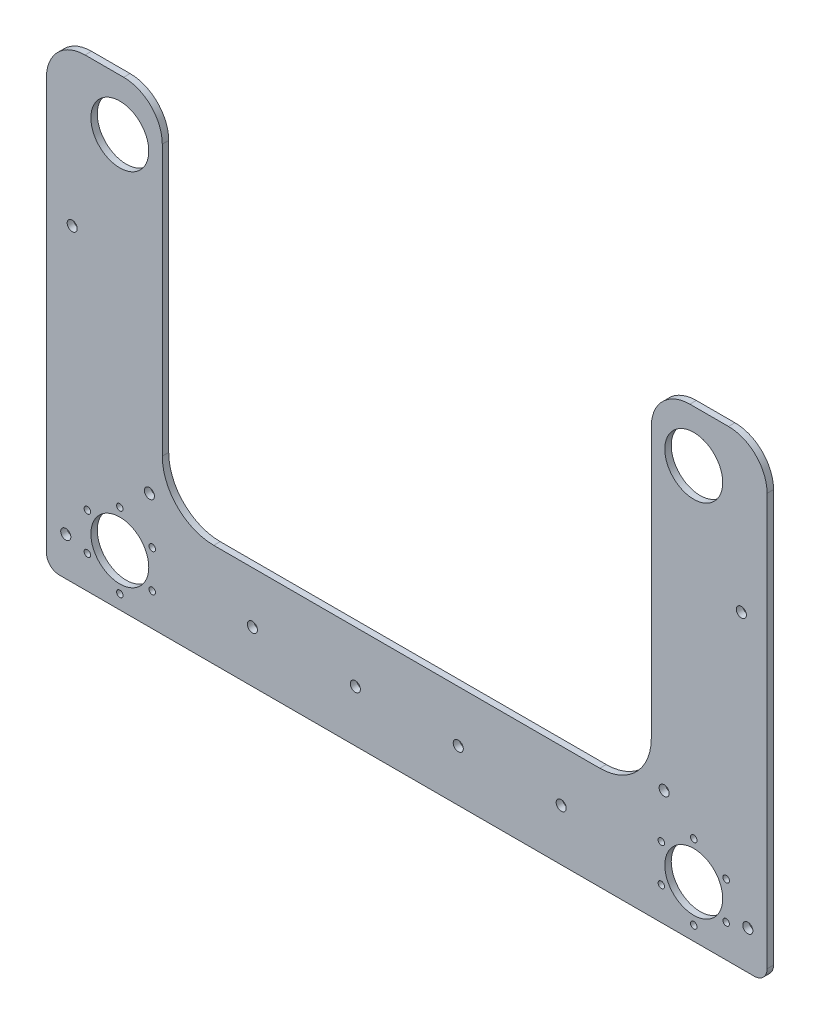
SolidWorks part; units mm, degrees
material "6061 Alloy"
ref_plane "Front Plane" through (0, 0, 0) normal (0, 0, 1) x (1, 0, 0)
ref_plane "Top Plane" through (0, 0, 0) normal (0, 1, 0) x (1, 0, 0)
ref_plane "Right Plane" through (0, 0, 0) normal (1, 0, 0) x (0, 0, -1)
sketch "Sketch1" plane through (0, 0, 0) normal (0, 0, 1) x (1, 0, 0)
  line L5 (120.65, -152.4) -> (120.65, -6.35)
  line L6 (127, 0) -> (171.45, 0) construction
  line L7 (177.8, -6.35) -> (177.8, -222.25)
  line L10 (0, -206.2199) -> (0, -63.6275) construction
  line L11 (-54.9244, 0) -> (300.6756, 0) construction
  line L13 (12.7, -177.8) -> (95.25, -177.8)
  line L14 (12.7, -228.6) -> (171.45, -228.6)
  line L15 (141.605, -25.4) -> (141.605, -84.2822) construction
  line L16 (141.605, -25.4) -> (141.605, -127) construction
  line L17 (-141.605, -25.4) -> (-141.605, -203.2) construction
  line L18 (-141.605, -25.4) -> (-141.605, -127) construction
  line L19 (-141.605, -19.05) -> (-141.605, -77.9322) construction
  line L20 (141.605, -25.4) -> (141.605, -203.2) construction
  line L22 (-120.65, -152.4) -> (-120.65, -6.35)
  line L23 (-12.7, -177.8) -> (-95.25, -177.8)
  line L24 (-12.7, -228.6) -> (-171.45, -228.6)
  line L25 (-177.8, -6.35) -> (-177.8, -222.25)
  line L26 (-12.7, -177.8) -> (12.7, -177.8)
  line L27 (-12.7, -228.6) -> (12.7, -228.6)
  line L28 (-177.8, -6.35) -> (-177.8, 6.35)
  line L29 (-165.1, 19.05) -> (-133.35, 19.05)
  line L30 (-120.65, 6.35) -> (-120.65, -6.35)
  line L31 (120.65, 6.35) -> (120.65, -6.35)
  line L32 (177.8, -6.35) -> (177.8, 6.35)
  line L33 (165.1, 19.05) -> (133.35, 19.05)
  arc A0 (95.25, -177.8) -> (120.65, -152.4) centre (95.25, -152.4) ccw
  arc A4 (120.65, -6.35) -> (127, 0) centre (127, -6.35) cw construction
  circle A8 centre (141.605, -25.4) radius 14.2875
  circle A9 centre (141.605, -25.4) radius 38.1 construction
  arc A10 (177.8, -6.35) -> (171.45, 0) centre (171.45, -6.35) ccw construction
  arc A11 (171.45, -228.6) -> (177.8, -222.25) centre (171.45, -222.25) ccw
  arc A14 (141.605, -82.55) -> (120.9214, -78.6758) centre (141.605, -25.4) ccw construction
  arc A15 (-141.605, -82.55) -> (-120.9214, -78.6758) centre (-141.605, -25.4) cw construction
  circle A16 centre (-141.605, -25.4) radius 38.1 construction
  circle A17 centre (-141.605, -25.4) radius 14.2875
  arc A19 (-95.25, -177.8) -> (-120.65, -152.4) centre (-95.25, -152.4) cw
  circle A20 centre (141.605, -127) radius 38.1 construction
  circle A21 centre (-141.605, -127) radius 38.1 construction
  arc A23 (-171.45, -228.6) -> (-177.8, -222.25) centre (-171.45, -222.25) cw
  circle A24 centre (-141.605, -203.2) radius 14.2875
  circle A25 centre (-141.605, -184.7225) radius 1.6002
  circle A26 centre (-125.603, -193.9612) radius 1.6002
  circle A27 centre (-125.603, -212.4388) radius 1.6002
  circle A28 centre (-141.605, -221.6775) radius 1.6002
  circle A29 centre (-157.607, -212.4388) radius 1.6002
  circle A30 centre (-157.607, -193.9612) radius 1.6002
  circle A31 centre (157.607, -212.4388) radius 1.6002
  circle A32 centre (157.607, -193.9612) radius 1.6002
  circle A33 centre (141.605, -184.7225) radius 1.6002
  circle A34 centre (125.603, -193.9612) radius 1.6002
  circle A35 centre (125.603, -212.4388) radius 1.6002
  circle A36 centre (141.605, -221.6775) radius 1.6002
  circle A37 centre (141.605, -203.2) radius 14.2875
  circle A39 centre (-76.2, -203.2) radius 2.4892
  circle A40 centre (76.2, -203.2) radius 2.4892
  circle A42 centre (-25.4, -203.2) radius 2.4892
  circle A43 centre (-127, -171.45) radius 2.4892
  arc A44 (-133.35, 19.05) -> (-120.65, 6.35) centre (-133.35, 6.35) cw
  arc A45 (-177.8, 6.35) -> (-165.1, 19.05) centre (-165.1, 6.35) cw
  arc A46 (133.35, 19.05) -> (120.65, 6.35) centre (133.35, 6.35) ccw
  arc A47 (177.8, 6.35) -> (165.1, 19.05) centre (165.1, 6.35) ccw
  circle A50 centre (-149.225, 6.35) radius 2.4892
  circle A51 centre (127, -171.45) radius 2.4892
  circle A53 centre (149.225, 6.35) radius 2.4892
  circle A54 centre (-168.275, -209.55) radius 2.4892
  circle A56 centre (168.275, -209.55) radius 2.4892
  circle A58 centre (-165.1, -76.2) radius 2.4892
  circle A59 centre (165.1, -76.2) radius 2.4892
  circle A60 centre (25.4, -203.2) radius 2.4892
  point P2 (177.8, -44.45)
  point P18 (177.8, 0)
  point P23 (177.8, -228.6)
  point P24 (177.8, -228.6)
  point P31 (177.8, 0)
  point P48 (-177.8, 0)
  point P49 (-177.8, -228.6)
  point P51 (-177.8, -44.45)
  point P78 (-141.605, -203.2)
  dimension "D6" = 25.4
  dimension "D7" = 6.35
  dimension "D8" = 6.35
  dimension "D9" = 177.8
  dimension "D10" = 28.575
  dimension "D12" = 76.2
  dimension "D13" = 57.15
  dimension "D15" = 28.575
  dimension "D18" = 76.2
  dimension "D21" = 3.2004
  dimension "D29" = 9.525
  dimension "D32" = 4.9784
  dimension "D35" = 4.9784
  dimension "D37" = 4.9784
  dimension "D40" = 12.7
  dimension "D43" = 4.9784
  dimension "D45" = 12.7
  dimension "D30" = 4.9784
  dimension "D41" = 4.9784
  dimension "D2" = 120.65
  dimension "D3" = 177.8
  dimension "D4" = 228.6
  dimension "D5" = 177.8
  dimension "D11" = 20.955
  dimension "`" = 25.4
  dimension "D14" = 57.15
  dimension "D16" = 184.15
  dimension "D17" = 101.6
  dimension "D19" = 25.4
  dimension "D20" = 101.6
  dimension "D22" = 0
  dimension "D23" = 18.4775
  dimension "D25" = 6.9225
  dimension "D26" = 19.05
  dimension "D27" = 25.4
  dimension "D28" = 25.4
  dimension "D31" = 95.25
  dimension "D33" = 12.7
  dimension "D34" = 25.4
  dimension "D38" = 57.15
  dimension "D39" = 19.05
  dimension "D42" = 6.35
  dimension "D44" = 28.575
  dimension "D46" = 25.4
  dimension "D24" = 6
extrude "Boss-Extrude3" add sketch "Sketch1" along normal blind 3.175
sketch "Sketch2" plane through (0, 0, 3.175) normal (0, 0, 1) x (1, 0, 0)
  line L0 (-133.35, 19.05) -> (-165.1, 19.05) construction
  line L1 (-177.8, 19.05) -> (177.8, 19.05)
  line L2 (-177.8, 19.05) -> (-177.8, 0)
  line L3 (-177.8, 0) -> (177.8, 0)
  line L4 (177.8, 19.05) -> (177.8, 0)
  line L5 (-177.8, 6.35) -> (-177.8, -222.25) construction
  line L6 (177.8, -222.25) -> (177.8, 6.35) construction
  dimension "D1" = 19.05
extrude "Cut-Extrude1" cut sketch "Sketch2" against normal through all
fillet "Fillet1" radius 19.05 4 edges at (177.8, 0, 1.5875) (120.65, 0, 1.5875) (-120.65, 0, 1.5875) (-177.8, 0, 1.5875)
